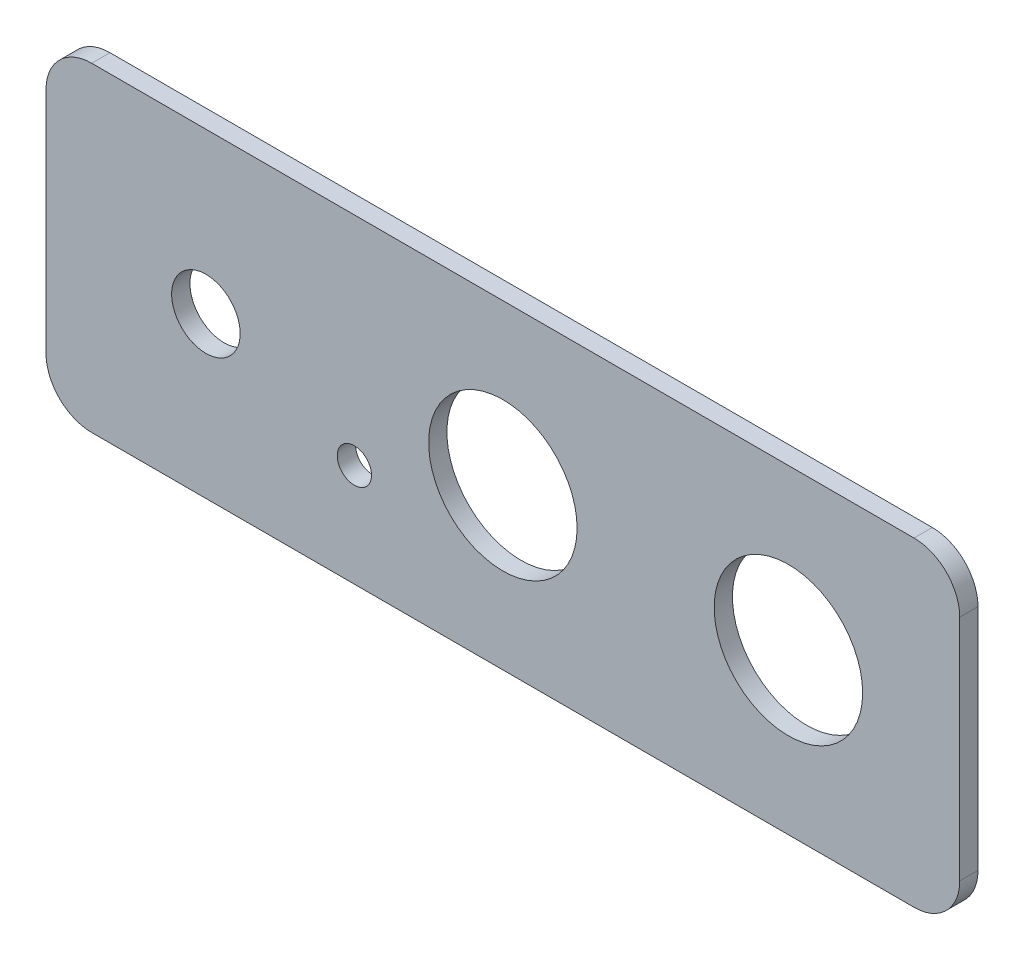
SolidWorks part; units mm, degrees
ref_plane "Front Plane" through (0, 0, 0) normal (0, 0, 1) x (1, 0, 0)
ref_plane "Top Plane" through (0, 0, 0) normal (0, 1, 0) x (1, 0, 0)
ref_plane "Right Plane" through (0, 0, 0) normal (1, 0, 0) x (0, 0, -1)
sketch "Sketch1" plane through (0, 0, 0) normal (0, 0, 1) x (1, 0, 0)
  line L0 (-40, 0) -> (40, 0) construction
  line L1 (-36, 14) -> (36, 14)
  line L2 (-40, 10) -> (-40, -10)
  line L3 (-36, -14) -> (36, -14)
  line L4 (40, 10) -> (40, -10)
  line L5 (-40, 14) -> (40, -14) construction
  line L6 (-40, -14) -> (40, 14) construction
  arc A0 (-40, -10) -> (-36, -14) centre (-36, -10) ccw
  arc A1 (36, -14) -> (40, -10) centre (36, -10) ccw
  arc A2 (36, 14) -> (40, 10) centre (36, 10) cw
  arc A3 (-36, 14) -> (-40, 10) centre (-36, 10) ccw
  circle A4 centre (-26, 0) radius 3
  circle A5 centre (0, 0) radius 6.5
  circle A6 centre (25, 0) radius 6.5
  circle A7 centre (-13, -5) radius 1.5
  point P0 (0, 0)
  dimension "D3" = 4
  dimension "D5" = 6
  dimension "D6" = 13
  dimension "D7" = 13
  dimension "D8" = 65
  dimension "D11" = 3
  dimension "D1" = 80
  dimension "D2" = 28
  dimension "D4" = 14
  dimension "D9" = 27
  dimension "D10" = 19
extrude "Boss-Extrude1" add sketch "Sketch1" along normal blind 1.6
